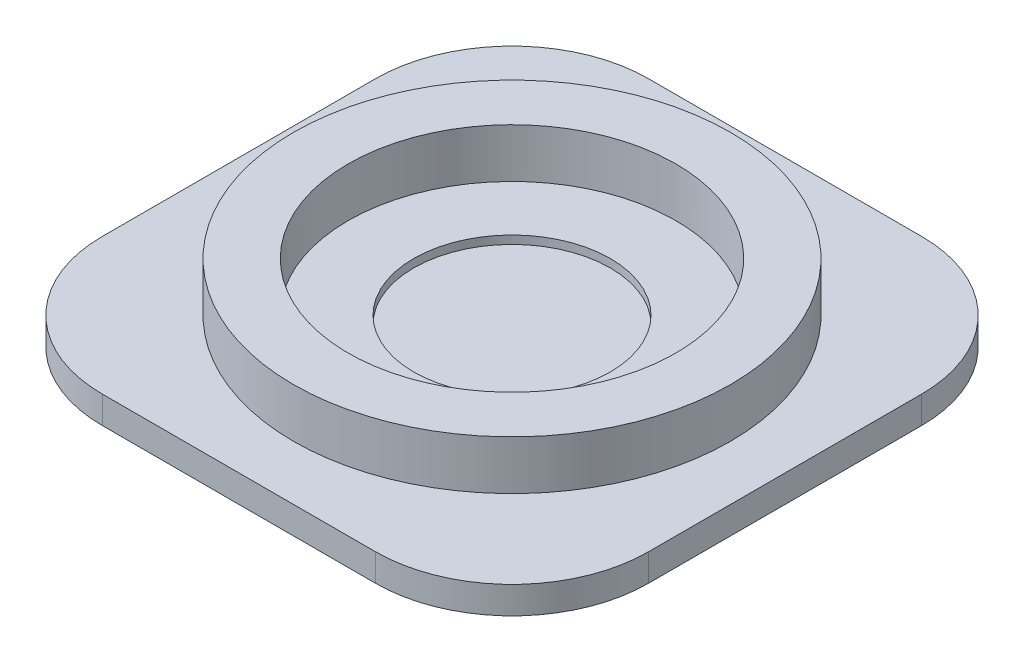
SolidWorks part; units mm, degrees
ref_plane "Plano frontal" through (0, 0, 0) normal (0, 0, 1) x (1, 0, 0)
ref_plane "Plano superior" through (0, 0, 0) normal (0, 1, 0) x (1, 0, 0)
ref_plane "Plano direito" through (0, 0, 0) normal (1, 0, 0) x (0, 0, -1)
sketch "Esboço1" plane through (0, 0, 0) normal (0, 1, 0) x (1, 0, 0)
  line L0 (-60.1693, -6.7946) -> (-10.1693, -6.7946) construction
  line L1 (-35.1693, 43.2054) -> (14.8307, 43.2054)
  line L2 (-60.1693, 18.2054) -> (-60.1693, -31.7946)
  line L3 (-35.1693, -56.7946) -> (14.8307, -56.7946)
  line L4 (39.8307, 18.2054) -> (39.8307, -31.7946)
  arc A0 (14.8307, -56.7946) -> (39.8307, -31.7946) centre (14.8307, -31.7946) ccw
  arc A1 (-35.1693, -56.7946) -> (-60.1693, -31.7946) centre (-35.1693, -31.7946) cw
  arc A2 (-35.1693, 43.2054) -> (-60.1693, 18.2054) centre (-35.1693, 18.2054) ccw
  arc A3 (39.8307, 18.2054) -> (14.8307, 43.2054) centre (14.8307, 18.2054) ccw
  dimension "D1" = 25
  dimension "D2" = 25
extrude "Ressalto-extrusão1" add sketch "Esboço1" along normal blind 5
sketch "Esboço2" plane through (0, 5, 0) normal (0, 1, 0) x (1, 0, 0)
  line L0 (-60.1693, -6.7946) -> (-10.1693, -6.7946) construction
  line L2 (-60.1693, 18.2054) -> (-60.1693, -31.7946) construction
  circle A0 centre (-10.1693, -6.7946) radius 30
  circle A1 centre (-10.1693, -6.7946) radius 27.5 construction
extrude "Extrusão-Fina1" add sketch "Esboço2" along normal blind 18 thin
sketch "Esboço3" plane through (0, 5, 0) normal (0, 1, 0) x (1, 0, 0)
  circle A0 centre (-10.1693, -6.7946) radius 18
ref_plane "Plano1" through (0, 9, 0) normal (0, 1, 0) x (1, 0, 0)
sketch "Esboço4" plane through (0, 9, 0) normal (0, 1, 0) x (1, 0, 0)
  circle A0 centre (-10.1693, -6.7946) radius 24
loft "Loft1" [suppressed] add profiles "Esboço3", "Esboço4"
fillet "Filete1" [suppressed] radius 10
sketch "Esboço5" [suppressed] plane through (0, 9, 0) normal (0, 1, 0) x (1, 0, 0)
  line L2 (-10.1693, -6.7946) -> (-10.1693, -60.6623)
  line L3 (-10.1693, -60.6623) -> (-68.526, -60.6623)
  line L4 (-68.526, -6.7946) -> (-68.526, -60.6623)
  line L6 (-10.1693, -6.7946) -> (-10.1693, 64.1014)
  line L7 (-10.1693, 64.1014) -> (-68.526, 64.1014)
  line L8 (-68.526, -6.7946) -> (-68.526, 64.1014)
extrude "Corte-extrusão1" [suppressed] cut sketch "Esboço5" against normal blind 29
sketch "Esboço7" plane through (0, 5, 0) normal (0, 1, 0) x (1, 0, 0)
  circle A0 centre (-10.1693, -6.7946) radius 18
extrude "Corte-extrusão2" cut sketch "Esboço7" against normal blind 1.5
sketch "Esboço10" [suppressed] plane through (0, 0, 0) normal (0, -1, 0) x (1, 0, 0)
  line L0 (-35.1693, 56.7946) -> (14.8307, 56.7946) construction
  line L1 (-10.1693, 56.7946) -> (-68.3198, 56.7946)
  line L2 (-10.1693, 56.7946) -> (-10.1693, -44.9428)
  line L3 (-10.1693, -44.9428) -> (-68.3198, -44.9428)
  line L4 (-68.3198, 56.7946) -> (-68.3198, -44.9428)
extrude "Corte-extrusão5" [suppressed] cut sketch "Esboço10" against normal blind 19.5
mirror "Espelhar5" [suppressed] about plane through (0, 9, 0) normal (0, 1, 0)
sketch "Esboço13" [suppressed] plane through (0, 18, 0) normal (0, 1, 0) x (1, 0, 0)
  circle A0 centre (-10.1693, 43.2054) radius 16
  point P3 (0, 0)
extrude "Corte-extrusão6" [suppressed] cut sketch "Esboço13" against normal blind 19.5
sketch "Esboço14" [suppressed] plane through (0, 18, 0) normal (0, 1, 0) x (1, 0, 0)
  circle A0 centre (-10.1693, -56.7946) radius 16
extrude "Corte-extrusão7" [suppressed] cut sketch "Esboço14" against normal blind 19.5 contours A0
sketch "Esboço15" [suppressed] plane through (0, 18, 0) normal (0, 1, 0) x (1, 0, 0)
  circle A0 centre (32.5083, 35.8831) radius 13.5
  arc A1 (39.8307, 18.2054) -> (14.8307, 43.2054) centre (14.8307, 18.2054) ccw construction
  circle A2 centre (32.5083, -49.4722) radius 13.5
  arc A3 (14.8307, -56.7946) -> (39.8307, -31.7946) centre (14.8307, -31.7946) ccw construction
extrude "Corte-extrusão8" [suppressed] cut sketch "Esboço15" against normal blind 19.5
sketch "Esboço16" plane through (0, 0, -43.2054) normal (0, 0, -1) x (-1, 0, 0)
  line L0 (-29.8307, 23) -> (-29.8307, 5) construction
  line L1 (-29.8307, 14) -> (64.7104, 14)
  line L3 (-29.8307, 40.8717) -> (64.7104, 40.8717)
  line L4 (64.7104, 14) -> (64.7104, 40.8717)
  line L6 (-29.8307, 14) -> (-67.5202, 14)
  line L8 (-29.8307, 40.8717) -> (-67.5202, 40.8717)
  line L9 (-67.5202, 14) -> (-67.5202, 40.8717)
extrude "Corte-extrusão9" cut sketch "Esboço16" against normal blind 128.5 contours L8 L9 L6 L1 L4 L3
